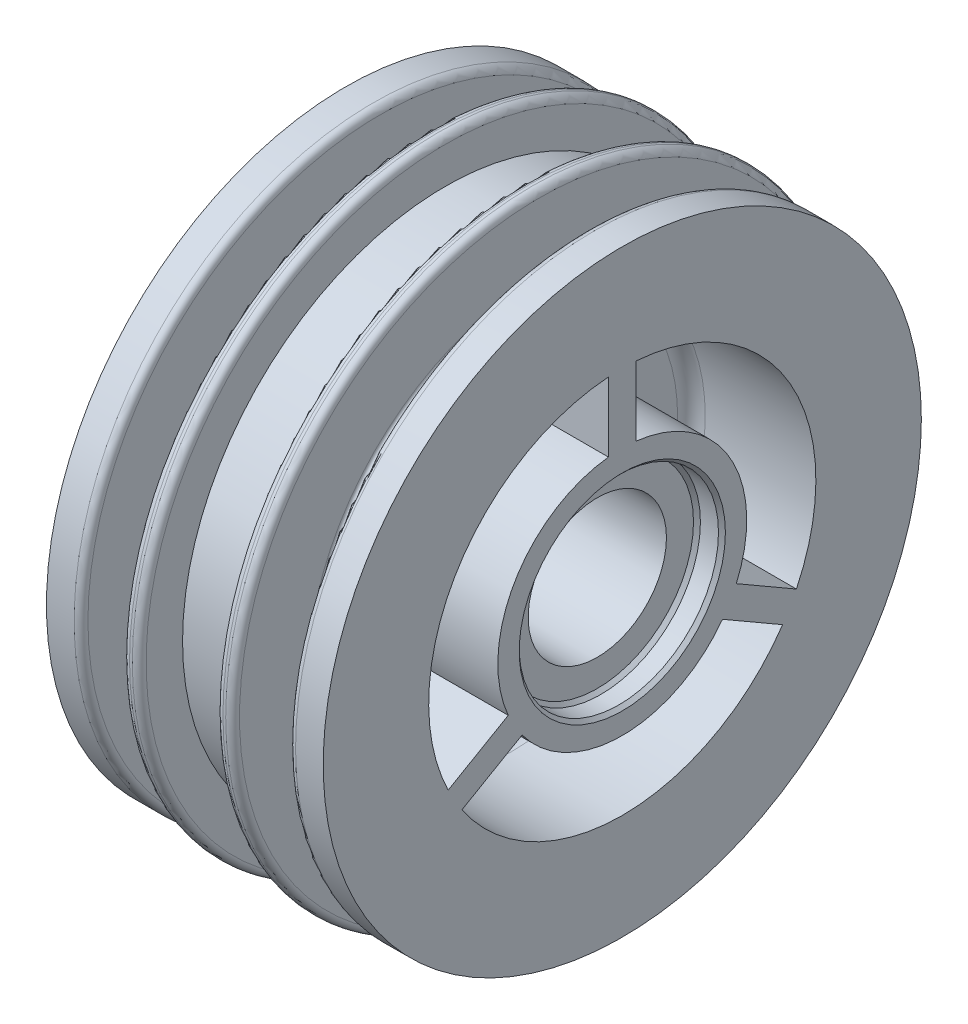
SolidWorks part; units mm, degrees
material "Aleación 1060"
ref_plane "Alzado" through (0, 0, 0) normal (0, 0, 1) x (1, 0, 0)
ref_plane "Planta" through (0, 0, 0) normal (0, 1, 0) x (1, 0, 0)
ref_plane "Vista lateral" through (0, 0, 0) normal (1, 0, 0) x (0, 0, -1)
sketch "Sketch1" plane through (0, 0, 0) normal (0, 0, 1) x (1, 0, 0)
  line L2 (-67.3493, 21.6278) -> (-69.8493, 21.6278)
  line L3 (-69.8493, 21.6278) -> (-69.8493, 16.5)
  line L4 (-69.8493, 16.5) -> (-73.3493, 16.5)
  line L5 (-73.3493, 16.5) -> (-73.3493, 22.1792)
  line L9 (-80.1493, 19) -> (-80.1493, 22.1338)
  line L10 (-80.1493, 22.1338) -> (-81.3493, 22.1338)
  line L11 (-81.3493, 22.1338) -> (-81.3493, 16.5)
  line L12 (-81.3493, 16.5) -> (-84.8493, 16.5)
  line L13 (-84.8493, 16.5) -> (-84.8493, 21.6419)
  line L14 (-84.8493, 21.6419) -> (-87.3493, 21.6419)
  line L19 (0, 0) -> (-91, 0) construction
  line L21 (-84.2084, 5) -> (-84.2084, 6)
  line L22 (-84.2084, 6) -> (-81.4084, 6)
  line L23 (-81.4084, 6) -> (-81.4084, 5)
  line L24 (-81.4084, 5) -> (-69.1559, 5)
  line L25 (-73.3493, 22.1792) -> (-74.5493, 22.1792)
  line L26 (-74.5493, 22.1792) -> (-74.5493, 19)
  line L27 (-74.5493, 19) -> (-80.1493, 19)
  line L28 (-87.3493, 21.6419) -> (-87.3493, 14)
  line L29 (-87.3493, 14) -> (-78.3493, 14)
  line L30 (-78.3493, 14) -> (-78.3493, 9)
  line L31 (-78.3493, 9) -> (-87.3493, 9)
  line L33 (-67.3493, 21.6278) -> (-67.3493, 14)
  line L34 (-67.3493, 14) -> (-76.3493, 14)
  line L35 (-76.3493, 14) -> (-76.3493, 9)
  line L36 (-76.3493, 9) -> (-67.3493, 9)
  line L38 (-87.3493, 9) -> (-87.3493, 7.2075)
  line L39 (-87.3493, 7.2075) -> (-85.7788, 7.2075)
  line L40 (-85.7788, 7.2075) -> (-85.7788, 5)
  line L41 (-85.7788, 5) -> (-84.2084, 5)
  line L42 (-67.3493, 7.2075) -> (-67.3493, 9)
  line L43 (-67.3493, 7.2075) -> (-69.1559, 7.2075)
  line L44 (-69.1559, 7.2075) -> (-69.1559, 5)
  point P24 (-81.4084, 5.5)
  dimension "D2" = 5
  dimension "D3" = 16.5
  dimension "D4" = 3.5
  dimension "D5" = 5
  dimension "D6" = 3.5
  dimension "D7" = 16.5
  dimension "D8" = 5.6
  dimension "D9" = 1.2
  dimension "D10" = 2.8
  dimension "D11" = 19
  dimension "D12" = 2.5
  dimension "D13" = 2.5
  dimension "D18" = 6
  dimension "D19" = 1.2
  dimension "D20" = 9
  dimension "D21" = 9
  dimension "D22" = 14
  dimension "D23" = 14
  dimension "D24" = 3
  dimension "D25" = 3
revolve "Revolución1" add sketch "Sketch1" angle 360 about L19
chamfer "Chaflán1" distance 0.25 angle 45 4 edges at (-81.4084, 0, -5) (-81.4084, 0, -6) (-84.2084, 0, -6) (-84.2084, 0, -5)
fillet "Redondeo1" radius 0.5 6 edges at (-69.8493, 0, -21.6278) (-73.3493, 0, -22.1792) (-74.5493, 0, -22.1792) (-80.1493, 0, -22.1338) (-81.3493, 0, -22.1338) (-84.8493, 0, -21.6419)
sketch "Sketch4" plane through (-87.3493, 0, 0) normal (-1, 0, 0) x (0, 0, 1)
  line L0 (0, 15.4784) -> (0, 7.6818)
  dimension "D1" = 7.7966
rib "Rib2" sketch "Sketch4" sketch "Sketch4" thickness 2 extrusion direction normal to sketch draft on no parameters "D1"=2
pattern_circular "CirPattern2" count 3 over 360 about axis through (0, 0, 0) along (1, 0, 0) of "Rib2"
sketch "Sketch5" plane through (-67.3493, 0, 0) normal (1, 0, 0) x (0, 0, -1)
  line L0 (0, 7.8837) -> (0, 15.1081)
rib "Rib3" sketch "Sketch5" sketch "Sketch5" thickness 2 extrusion direction normal to sketch draft on no parameters "D1"=2
pattern_circular "CirPattern3" count 3 over 360 about axis through (0, 0, 0) along (1, 0, 0) of "Rib3"
fillet "Fillet4" radius 1 12 edges at (-82.8493, 8.775, -2) (-82.8493, 13.8564, -2) (-82.8493, 14, 0) (-82.8493, 9, 0) (-82.8493, -6.1195, -6.5993) (-82.8493, -8.6603, -11) (-82.8493, -7, -12.1244) (-82.8493, -4.5, -7.7942) (-82.8493, -2.6554, 8.5993) (-82.8493, -5.1962, 13) (-82.8493, -7, 12.1244) (-82.8493, -4.5, 7.7942)
fillet "Fillet5" radius 1 36 edges at (-76.3493, 7, 12.1244) (-76.3493, 4.5, 7.7942) (-76.3493, 11.4543, 1) (-76.3493, 11.4543, -1) (-76.3493, 7, -12.1244) (-76.3493, 4.5, -7.7942) (-76.3493, -4.8611, -10.4197) (-76.3493, -6.5932, -9.4197) (-76.3493, -14, 0) (-76.3493, -9, 0) (-76.3493, -6.5932, 9.4197) (-76.3493, -4.8611, 10.4197) (-78.3493, -5.7278, 9.9209) (-78.3493, -13.9575, 1.09) (-78.3493, -7.2792, -8.6079) (-78.3493, -8.953, 0.9188) (-78.3493, -4.8633, 7.9067) (-78.3493, -6.3738, -6.6521) (-78.3493, -8.7778, -10.4439) (-78.3493, -7.1253, 11.7001) (-78.3493, 7.9227, 11.5426) (-78.3493, -3.8151, 10.6079) (-78.3493, 11.4557, 0) (-78.3493, 5.2722, 7.2941) (-78.3493, 9.2791, 0.2584) (-78.3493, 13.6953, 0.3206) (-78.3493, -2.574, 8.8459) (-78.3493, -4.6558, 12.8237) (-78.3493, 3.6808, -8.2129) (-78.3493, 11.0943, -2) (-78.3493, 6.0348, -12.6325) (-78.3493, -5.7278, -9.9209) (-78.3493, 13.4336, -2.3798) (-78.3493, -4.4158, -8.1651) (-78.3493, -6.57, -12.0208) (-78.3493, 8.9478, -2.1938)
chamfer "Chaflán2" distance 0.25 angle 45 4 edges at (-69.1559, 0, -7.2075) (-85.7788, 0, -7.2075) (-87.3493, 0, -7.2075) (-67.3493, 0, -7.2075)
fillet "Redondeo3" radius 0.25 4 edges at (-69.8493, 0, -16.5) (-73.3493, 0, -16.5) (-81.3493, 0, -16.5) (-84.8493, 0, -16.5)
ref_plane "Plano1" through (-87, 0, 0) normal (1, 0, 0) x (0, 0, -1)
sketch "Croquis1" plane through (-87, 0, 0) normal (1, 0, 0) x (0, 0, -1)
  line L0 (0, 0) -> (0, 8.1786) construction
  line L1 (0, 11) -> (0, -11) construction
ref_plane "Plano2" through (-68, 0, 0) normal (1, 0, 0) x (0, 0, -1)
